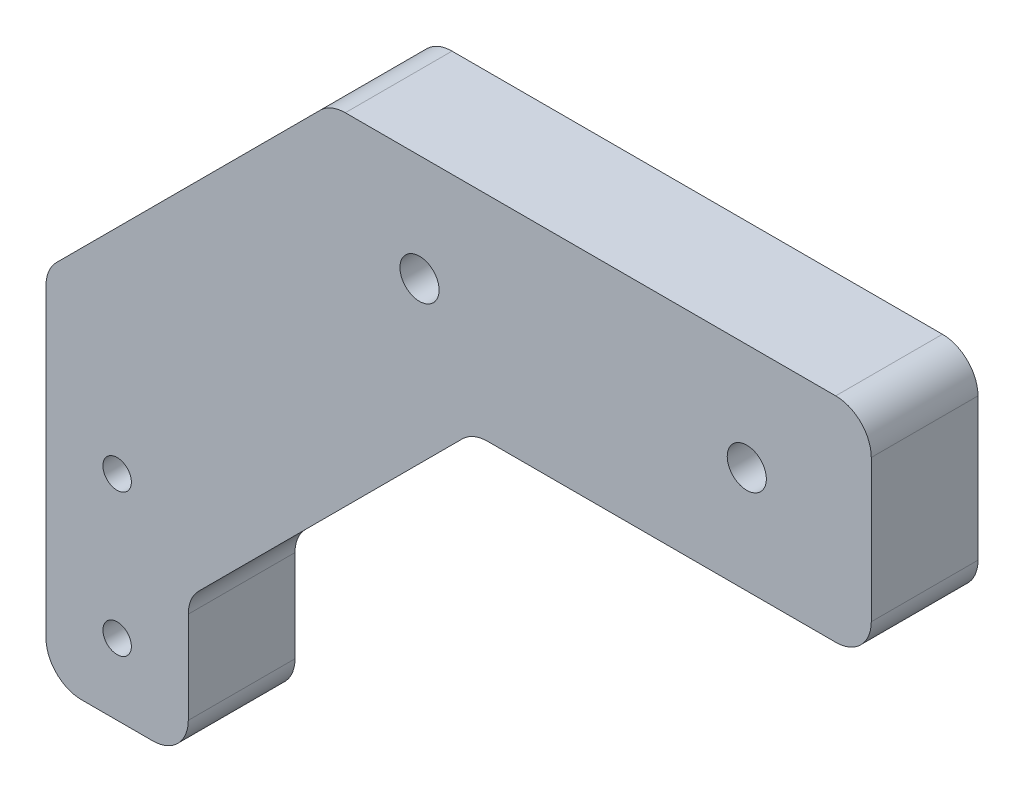
SolidWorks part; units mm, degrees
ref_plane "Front Plane" through (0, 0, 0) normal (0, 0, 1) x (1, 0, 0)
ref_plane "Top Plane" through (0, 0, 0) normal (0, 1, 0) x (1, 0, 0)
ref_plane "Right Plane" through (0, 0, 0) normal (1, 0, 0) x (0, 0, -1)
sketch "Sketch1" plane through (0, 0, 0) normal (0, 0, 1) x (1, 0, 0)
  line L0 (0, -60) -> (0, 30)
  line L1 (0, -8.25) -> (0, 8.25) construction
  line L2 (0, 30) -> (116, 30)
  line L3 (116, 30) -> (116, 0)
  line L4 (8.25, 0) -> (-8.25, 0) construction
  line L5 (116, 0) -> (20, 0)
  line L6 (20, 0) -> (20, -60)
  line L7 (20, -60) -> (0, -60)
  dimension "D1" = 30
  dimension "D2" = 116
  dimension "D3" = 60
  dimension "D4" = 20
extrude "Boss-Extrude1" add sketch "Sketch1" along normal blind 15
sketch "Sketch2" plane through (0, 0, 0) normal (0, 0, 1) x (1, 0, 0)
  line L1 (116, 30) -> (0, 30) construction
  line L2 (0, -60) -> (20, -60) construction
  line L3 (0, -8.25) -> (0, 8.25) construction
  circle A0 centre (10, -50) radius 2
  circle A1 centre (10, -30) radius 2
  circle A2 centre (52.5, 15) radius 2.75
  circle A3 centre (98.5, 15) radius 2.75
  dimension "D1" = 4
  dimension "D2" = 4
  dimension "D3" = 5.5
  dimension "D4" = 5.5
  dimension "D5" = 42.5
  dimension "D6" = 46
  dimension "D7" = 15
  dimension "D8" = 15
  dimension "D9" = 10
  dimension "D10" = 10
  dimension "D11" = 10
  dimension "D12" = 20
extrude "Cut-Extrude3" cut sketch "Sketch2" along normal up to next
chamfer "Chamfer1" distance 40 angle 45 2 edges at (0, 30, 7.5) (20, 0, 7.5)
fillet "Fillet1" radius 5 8 edges at (40, 30, 7.5) (0, -10, 7.5) (0, -60, 7.5) (20, -60, 7.5) (20, -40, 7.5) (60, 0, 7.5) (116, 0, 7.5) (116, 30, 7.5)
